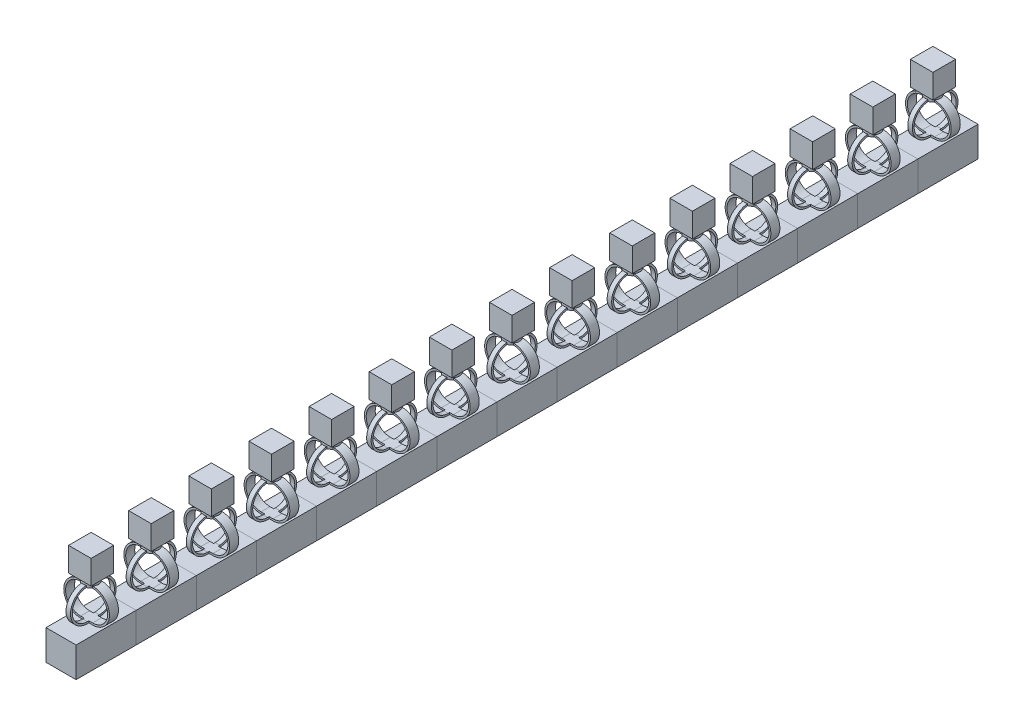
SolidWorks part; units mm, degrees
material "PLA"
ref_plane "Front Plane" through (0, 0, 0) normal (0, 0, 1) x (1, 0, 0)
ref_plane "Top Plane" through (0, 0, 0) normal (0, 1, 0) x (1, 0, 0)
ref_plane "Right Plane" through (0, 0, 0) normal (1, 0, 0) x (0, 0, -1)
sketch "Sketch1" plane through (0, 0, 0) normal (0, 0, 1) x (1, 0, 0)
  line L1 (-5, 5) -> (5, 5)
  line L2 (-5, 5) -> (-5, -5)
  line L3 (-5, -5) -> (5, -5)
  line L4 (5, 5) -> (5, -5)
  line L5 (-5, 5) -> (5, -5) construction
  line L6 (-5, -5) -> (5, 5) construction
  point P0 (0, 0)
  dimension "D1" = 10
  dimension "D2" = 10
extrude "Boss-Extrude1" add sketch "Sketch1" along normal mid plane 20
sketch "Sketch2" plane through (0, 0, 0) normal (0, 0, 1) x (1, 0, 0)
  line L0 (-5, 0) -> (5, 0) construction
  line L1 (-5, 5) -> (-5, -5) construction
  line L2 (5, -5) -> (5, 5) construction
  line L3 (0, 5.6) -> (-2, 5.6)
  line L4 (-2, 15.6) -> (0, 15.6)
  line L5 (0, 5) -> (-2, 5)
  line L6 (-2, 16.2) -> (0, 16.2)
  line L8 (0, 16.2) -> (0, 15.6)
  line L9 (5, 5) -> (-5, 5) construction
  line L10 (0, 5.6) -> (0, 5)
  arc A0 (-2, 5.6) -> (-2, 15.6) centre (-2, 10.6) cw
  arc A1 (-2, 5) -> (-2, 16.2) centre (-2, 10.6) cw
  dimension "D1" = 5
  dimension "t" = 0.6
  dimension "D2" = 2
extrude "Boss-Extrude2" add sketch "Sketch2" along normal mid plane 3
mirror "Mirror1" about plane through (0, 0, 0) normal (1, 0, 0) of "Boss-Extrude2"
sketch "Sketch3" plane through (0, 0, 0) normal (1, 0, 0) x (0, 0, -1)
  line L0 (0, 5) -> (-2, 5)
  line L2 (-10, 5) -> (10, 5) construction
  line L3 (-2, 16.2) -> (0, 16.2)
  line L4 (-1.5, 16.2) -> (1.5, 16.2) construction
  line L5 (0, 5.6) -> (-2, 5.6)
  line L6 (-2, 15.6) -> (0, 15.6)
  line L7 (0, 15.6) -> (0, 16.2)
  line L8 (0, 5.6) -> (0, 5)
  arc A0 (-2, 5) -> (-2, 16.2) centre (-2, 10.6) cw
  arc A1 (-2, 5.6) -> (-2, 15.6) centre (-2, 10.6) cw
  dimension "D2" = 5.6
  dimension "D3" = 5
  dimension "D1" = 2
extrude "Boss-Extrude3" add sketch "Sketch3" along normal mid plane 1.5
mirror "Mirror2" about plane through (0, 0, 0) normal (0, 0, 1) of "Boss-Extrude3"
sketch "Sketch4" plane through (0, 16.2, 0) normal (0, 1, 0) x (1, 0, 0)
  line L1 (-3.75, 3.75) -> (3.75, 3.75)
  line L2 (-3.75, 3.75) -> (-3.75, -3.75)
  line L3 (-3.75, -3.75) -> (3.75, -3.75)
  line L4 (3.75, 3.75) -> (3.75, -3.75)
  line L5 (-3.75, 3.75) -> (3.75, -3.75) construction
  line L6 (-3.75, -3.75) -> (3.75, 3.75) construction
  point P0 (0, 0)
  dimension "D1" = 7.5
  dimension "D2" = 7.5
extrude "Boss-Extrude4" add sketch "Sketch4" along normal blind 10 separate body
chamfer "Chamfer1" distance 2 angle 45 4 edges at (3.75, 16.2, 0) (0, 16.2, 3.75) (-3.75, 16.2, 0) (0, 16.2, -3.75)
sketch "Sketch5" plane through (0, 15.6, 0) normal (0, -1, 0) x (1, 0, 0)
  circle A0 centre (0, 0) radius 2.4749
extrude "Boss-Extrude5" add sketch "Sketch5" against normal up to next
pattern_linear "LPattern2" count 15 spacing 20 along (0, 0, 1) of bodies 108
equation "\"a\"= 10mm'Dimenzija nosilca"
equation "\"w\"= 1.5mm'Širina vzmeti"
equation "\"t\"= 0.6mm'Debelina vzmeti"
equation "\"r\"= 5mm'Polmer loka vmzeti"
equation "\"rr\"= 10mm'Polmer resonatorja"
equation "\"L\"= 20mm'Dolžina bazne celice"
equation "\"t@Sketch2\"=\"t\""
equation "\"D1@Sketch2\"=\"r\""
equation "\"D1@Sketch1\"=\"a\""
equation "\"D2@Sketch1\"=\"a\""
equation "\"D1@Boss-Extrude1\"=\"L\""
equation "\"D2@Sketch3\"=\"r\"+\"t\""
equation "\"D3@Sketch3\"=\"r\""
equation "\"D1@Boss-Extrude3\"=\"w\""
equation "\"N\"= 15'Amount of cells"
equation "\"D3@LPattern2\"=\"L\""
equation "\"D1@LPattern2\"=\"N\""
